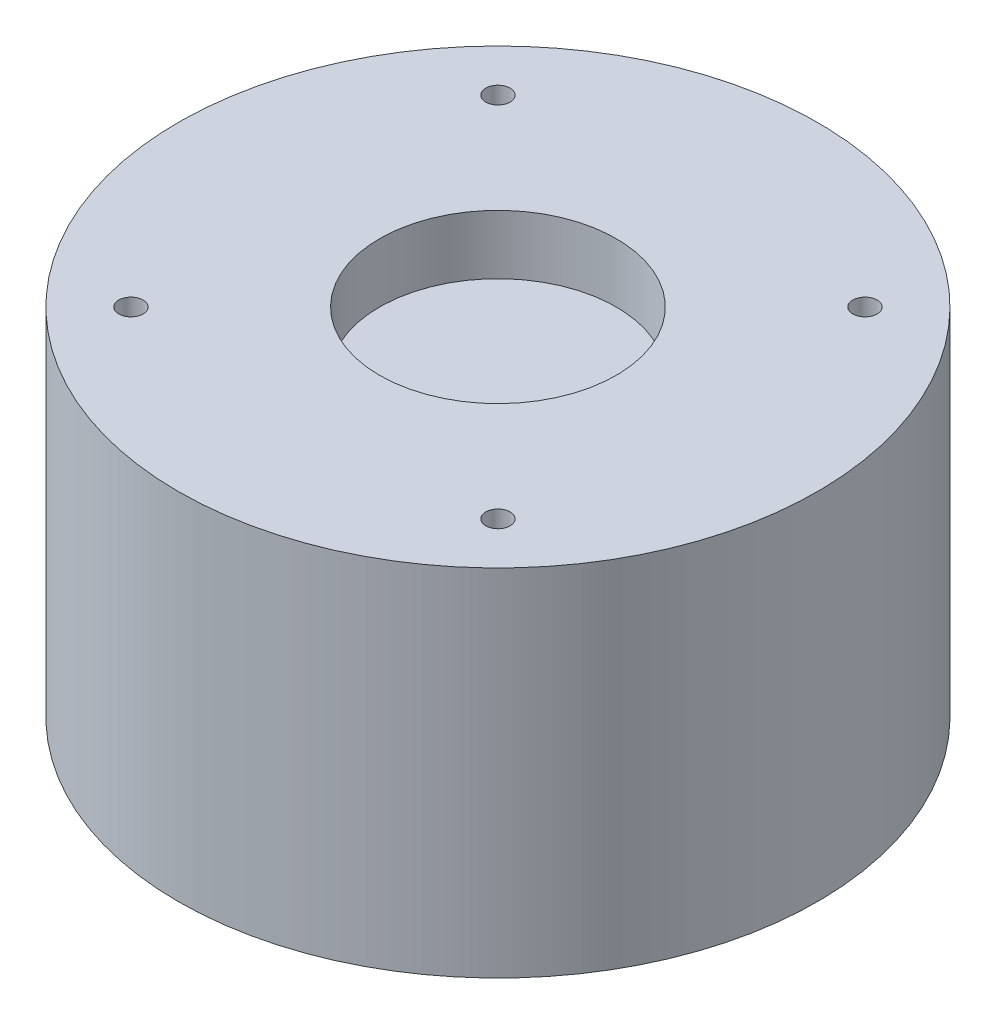
SolidWorks part; units mm, degrees
ref_plane "前视基准面" through (0, 0, 0) normal (0, 0, 1) x (1, 0, 0)
ref_plane "上视基准面" through (0, 0, 0) normal (0, 1, 0) x (1, 0, 0)
ref_plane "右视基准面" through (0, 0, 0) normal (1, 0, 0) x (0, 0, -1)
sketch "草图1" plane through (0, 0, 0) normal (0, 1, 0) x (1, 0, 0)
  circle A0 centre (0, 0) radius 27
  dimension "D1" = 54
extrude "凸台-拉伸1" add sketch "草图1" along normal blind 30
sketch "草图4" plane through (0, 0, 0) normal (0, -1, 0) x (1, 0, 0)
  line L1 (-15.5, -15.5) -> (15.5, -15.5)
  line L2 (-15.5, -15.5) -> (-15.5, 15.5)
  line L3 (-15.5, 15.5) -> (15.5, 15.5)
  line L4 (15.5, -15.5) -> (15.5, 15.5)
  line L5 (-15.5, -15.5) -> (15.5, 15.5) construction
  line L6 (-15.5, 15.5) -> (15.5, -15.5) construction
  point P0 (0, 0)
  dimension "D1" = 31
  dimension "D2" = 31
hole_wizard "M2.5 螺纹孔1" positions "草图6" profile "草图5" tap size "M2.5" standard "GB" end condition through all
sketch "草图6" plane through (0, 0, 0) normal (0, -1, 0) x (-1, 0, 0)
  point P1 (15.5, 15.5)
  point P4 (-15.5, 15.5)
  point P7 (-15.5, -15.5)
  point P10 (15.5, -15.5)
sketch "草图5" plane through (-15.5, 0, -15.5) normal (1, 0, 0) x (0, 0, -1)
  line L0 (0, 0) -> (0, 30)
  line L1 (0, 30) -> (1.025, 30)
  line L2 (1.025, 30) -> (1.025, 0)
  line L5 (1.025, 0) -> (0, 0)
  line L11 (0, -6.35) -> (0, 107.95) construction
  dimension "通孔螺纹孔钻头直径" = 2.05
  dimension "通孔螺纹孔钻头深度" = 30
cosmetic thread "孔螺蚊线1"
cosmetic thread "孔螺蚊线2"
cosmetic thread "孔螺蚊线3"
cosmetic thread "孔螺蚊线4"
sketch "草图7" plane through (0, 0, 0) normal (0, -1, 0) x (1, 0, 0)
  circle A0 centre (0, 0) radius 2.5
extrude "切除-拉伸1" cut sketch "草图7" against normal blind 24
sketch "草图8" plane through (0, 30, 0) normal (0, 1, 0) x (1, 0, 0)
  circle A0 centre (0, 0) radius 10
extrude "切除-拉伸2" cut sketch "草图8" against normal blind 5
